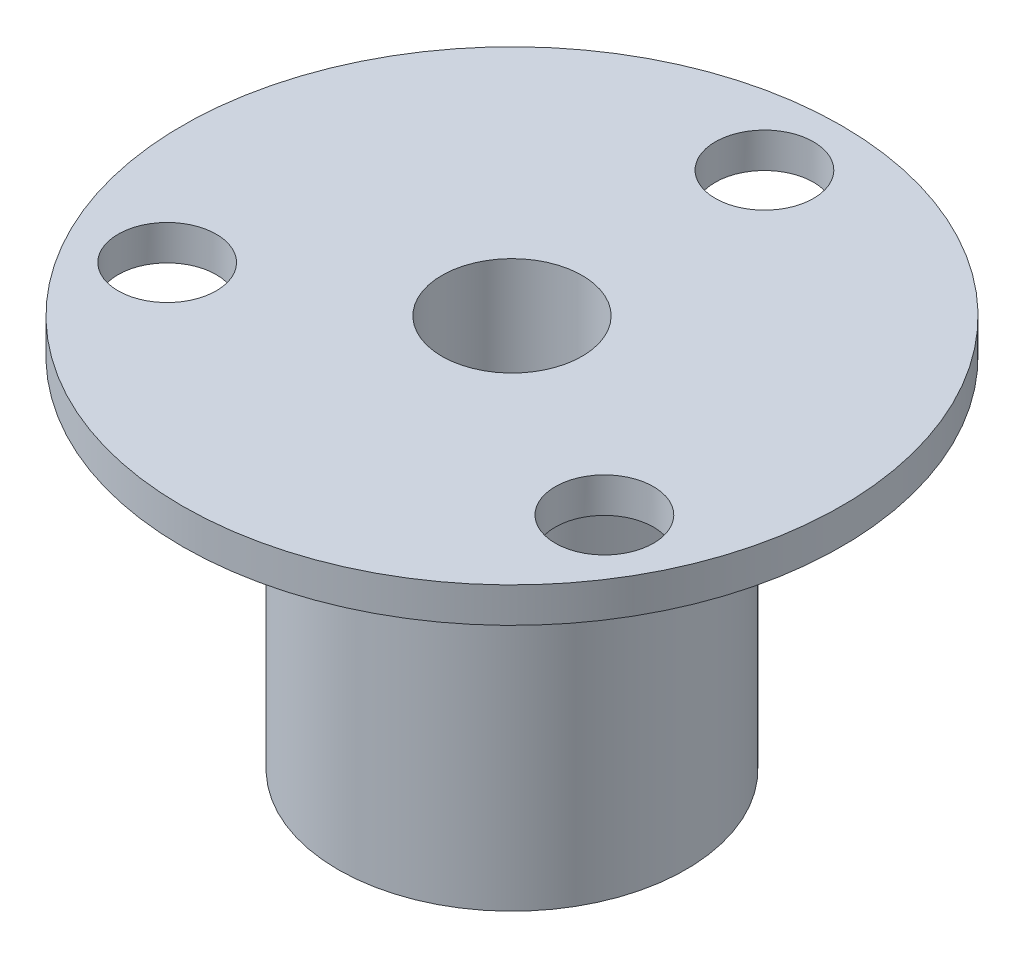
SolidWorks part; units mm, degrees
ref_plane "Front Plane" through (0, 0, 0) normal (0, 0, 1) x (1, 0, 0)
ref_plane "Top Plane" through (0, 0, 0) normal (0, 1, 0) x (1, 0, 0)
ref_plane "Right Plane" through (0, 0, 0) normal (1, 0, 0) x (0, 0, -1)
sketch "Sketch1" plane through (0, 0, 0) normal (0, 0, 1) x (1, 0, 0)
  line L0 (0, 0) -> (0, 16.8) construction
  line L1 (0, 16.8) -> (2, 16.8)
  line L2 (2, 16.8) -> (2, 14)
  line L3 (2, 14) -> (11.75, 14)
  line L4 (11.75, 14) -> (11.75, 12.75)
  line L5 (11.75, 12.75) -> (6.2, 12.75)
  line L6 (6.2, 12.75) -> (6.2, 0)
  line L7 (6.2, 0) -> (0, 0)
  line L8 (0, 16.8) -> (0, 0)
  point P9 (3.9, 12.186)
  dimension "D1" = 2.8
  dimension "D2" = 1.25
  dimension "D3" = 16.8
  dimension "D4" = 6.2
  dimension "D5" = 11.75
  dimension "D6" = 2
revolve "Revolve1" add sketch "Sketch1" angle 360 about L0
sketch "Sketch2" plane through (0, 16.8, 0) normal (0, 1, 0) x (1, 0, 0)
  circle A0 centre (0, 0) radius 2.5
  dimension "D1" = 5
extrude "Cut-Extrude1" cut sketch "Sketch2" against normal blind 56
sketch "Sketch3" plane through (0, 14, 0) normal (0, 1, 0) x (1, 0, 0)
  circle A0 centre (0, 0) radius 9 construction
  circle A1 centre (0, 9) radius 1.75
  circle A2 centre (7.7942, -4.5) radius 1.75
  circle A3 centre (-7.7942, -4.5) radius 1.75
  point P11 (0, 0)
  dimension "D1" = 18
  dimension "D2" = 3.5
  dimension "D3" = 3
extrude "Cut-Extrude2" cut sketch "Sketch3" against normal blind 10
